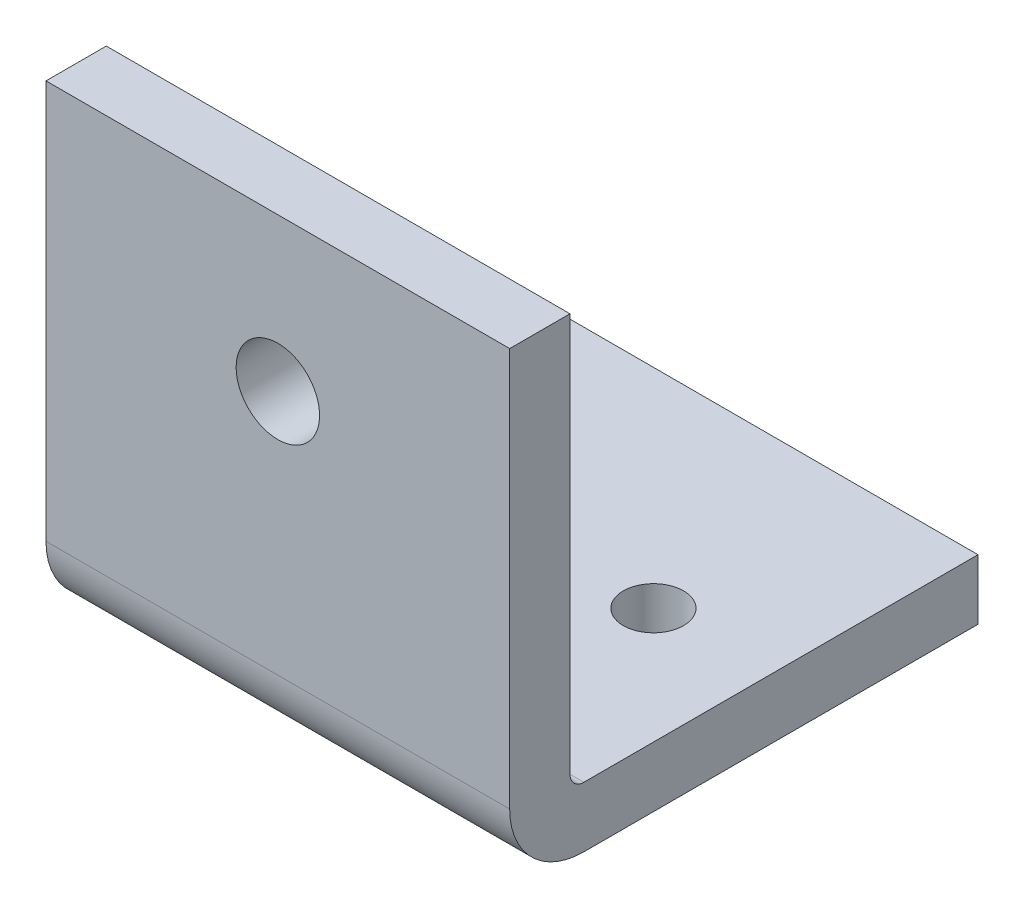
SolidWorks part; units mm, degrees
ref_plane "Piano frontale" through (0, 0, 0) normal (0, 0, 1) x (1, 0, 0)
ref_plane "Piano superiore" through (0, 0, 0) normal (0, 1, 0) x (1, 0, 0)
ref_plane "Piano destro" through (0, 0, 0) normal (1, 0, 0) x (0, 0, -1)
sketch "Schizzo2" plane through (0, 0, 0) normal (1, 0, 0) x (0, 0, -1)
  line L0 (0, 102) -> (0, 16)
  line L1 (16, 0) -> (101, 0)
  arc A0 (0, 16) -> (16, 0) centre (16, 16) ccw
  point P6 (0, 0)
  dimension "D3" = 16
  dimension "D1" = 102
  dimension "D2" = 101
extrude "Estrusione-Sottile1" add sketch "Schizzo2" along normal mid plane 100 thin thin type one direction reverse wall 13
sketch "Schizzo4" plane through (0, 13, 0) normal (0, 1, 0) x (1, 0, 0)
  line L0 (-50, 16) -> (-50, 101) construction
  line L1 (50, 101) -> (-50, 101) construction
  circle A0 centre (-25, 56) radius 6.5
  circle A1 centre (25, 56) radius 6.5
  point P6 (0, 0)
  point P7 (0, 0)
  point P10 (0, 0)
  point P11 (25, 56)
  dimension "D1" = 25
  dimension "D4" = 13
  dimension "D5" = 13
  dimension "D2" = 50
  dimension "D3" = 45
extrude "Taglio-Estrusione1" cut sketch "Schizzo4" against normal through all
sketch "Schizzo5" plane through (0, 0, -13) normal (0, 0, -1) x (-1, 0, 0)
  line L0 (0, 102) -> (0, 0) construction
  line L1 (-50, 102) -> (50, 102) construction
  line L2 (-50, 0) -> (50, 0) construction
  circle A0 centre (0, 69) radius 9
  dimension "D2" = 18
  dimension "D1" = 33
extrude "Taglio-Estrusione2" cut sketch "Schizzo5" against normal through all
ref_plane "Piano1" through (25, 0, 0) normal (1, 0, 0) x (0, 0, -1)
sketch "Schizzo6" plane through (25, 0, 0) normal (1, 0, 0) x (0, 0, -1)
  line L0 (13, 33) -> (33, 13)
  line L1 (13, 102) -> (13, 16) construction
  line L2 (16, 13) -> (101, 13) construction
  dimension "D1" = 20
  dimension "D2" = 20
rib "Nervatura2" sketch "Schizzo6" sketch "Schizzo6" thickness 5 extrusion direction parallel to sketch draft on no parameters "D1"=5
mirror "Specchia1" about plane through (0, 0, 0) normal (1, 0, 0) of "Nervatura2"
